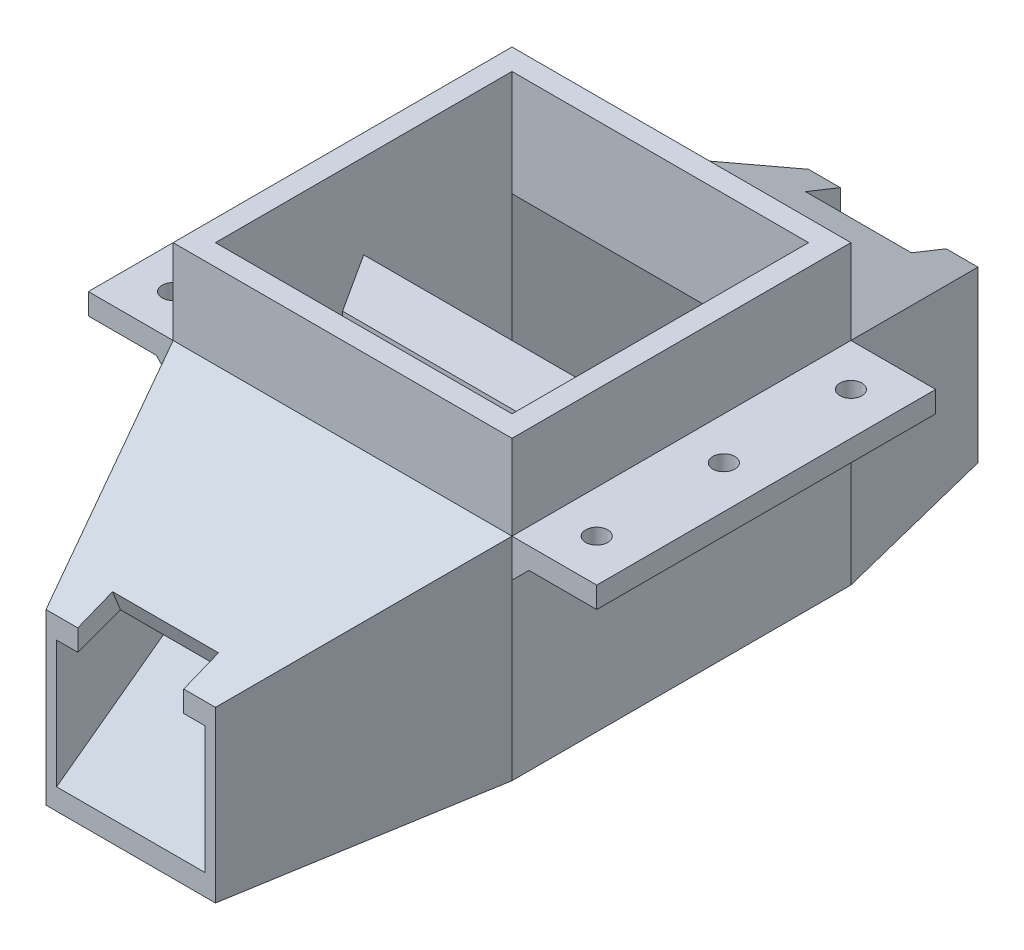
SolidWorks part; units mm, degrees
ref_plane "前视基准面" through (0, 0, 0) normal (0, 0, 1) x (1, 0, 0)
ref_plane "上视基准面" through (0, 0, 0) normal (0, 1, 0) x (1, 0, 0)
ref_plane "右视基准面" through (0, 0, 0) normal (1, 0, 0) x (0, 0, -1)
sketch "草图2" plane through (0, 0, 0) normal (0, 0, 1) x (1, 0, 0)
  line L0 (0, 0) -> (0, -45)
  line L1 (0, -45) -> (80, -45)
  line L2 (80, -45) -> (80, 0)
  line L3 (80, 0) -> (100, 0)
  line L4 (100, 0) -> (100, 5)
  line L5 (100, 5) -> (80, 5)
  line L6 (80, 5) -> (80, 25)
  line L7 (0, 25) -> (80, 25)
  line L13 (0, 25) -> (0, 5)
  line L14 (0, 5) -> (-20, 5)
  line L15 (-20, 5) -> (-20, 0)
  line L16 (-20, 0) -> (0, 0)
  dimension "D2" = 80
  dimension "D3" = 20
  dimension "D4" = 20
  dimension "D7" = 45
  dimension "D8" = 5
  dimension "D9" = 80
  dimension "D11" = 20
  dimension "D12" = 20
extrude "凸台-拉伸1" add sketch "草图2" along normal blind 80
sketch "草图4" plane through (0, 5, 0) normal (0, 1, 0) x (1, 0, 0)
  line L0 (0, 0) -> (-20, 0) construction
  line L3 (-20, -80) -> (-20, 0) construction
  circle A0 centre (-10, -40) radius 2.6
  circle A1 centre (-10, -70) radius 2.6
  circle A2 centre (-10, -10) radius 2.6
  circle A3 centre (90, -10) radius 2.6
  circle A4 centre (90, -40) radius 2.6
  circle A5 centre (90, -70) radius 2.6
  dimension "D1" = 5.2
  dimension "D2" = 5.2
  dimension "D5" = 5.2
  dimension "D3" = 40
  dimension "D4" = 30
  dimension "D6" = 10
  dimension "D7" = 10
  dimension "D8" = 10
  dimension "D9" = 2
extrude "切除-拉伸2" cut sketch "草图4" against normal blind 150
chamfer "倒角1" distance 4 angle 45 1 edges at (80, 0, 40)
chamfer "倒角2" distance 4 angle 45 1 edges at (0, 0, 40)
ref_plane "基准面1" through (0, 0, 40) normal (0, 0, 1) x (1, 0, 0)
sketch "草图8" plane through (0, 25, 0) normal (0, 1, 0) x (1, 0, 0)
  line L3 (80, -80) -> (0, -80) construction
  line L4 (5, -75) -> (75, -75)
  line L5 (5, -75) -> (5, -5)
  line L6 (5, -5) -> (75, -5)
  line L7 (75, -75) -> (75, -5)
  line L8 (0, -80) -> (0, 0) construction
  dimension "D1" = 5
  dimension "D3" = 70
  dimension "D2" = 5
  dimension "D4" = 70
extrude "切除-拉伸3" cut sketch "草图8" against normal blind 70
sketch "草图10" plane through (0, 0, 0) normal (0, 0, -1) x (-1, 0, 0)
ref_plane "基准面2" through (0, 0, -50) normal (0, 0, -1) x (-1, 0, 0)
sketch "草图17" plane through (0, 0, 0) normal (0, 0, -1) x (-1, 0, 0)
  line L1 (-80, 5) -> (0, 5)
  line L2 (-80, 5) -> (-80, -45)
  line L3 (-80, -45) -> (0, -45)
  line L4 (0, 5) -> (0, -45)
sketch "草图19" plane through (0, 0, -50) normal (0, 0, -1) x (-1, 0, 0)
  line L0 (-80, 5) -> (-80, -45) construction
  line L1 (-60, -15) -> (-20, -15)
  line L2 (-60, -15) -> (-60, -55)
  line L3 (-60, -55) -> (-20, -55)
  line L4 (-20, -15) -> (-20, -55)
  line L5 (-80, 5) -> (0, 5) construction
  dimension "D1" = 40
  dimension "D2" = 40
  dimension "D3" = 20
  dimension "D4" = 20
loft "放样3" add profiles "草图19", "草图17"
sketch "草图20" plane through (0, 0, 5) normal (0, 0, 1) x (1, 0, 0)
  line L0 (5, -45) -> (5, 25) construction
  line L1 (5, 0) -> (75, 0)
  line L2 (5, 0) -> (5, -40)
  line L3 (5, -40) -> (75, -40)
  line L4 (75, 0) -> (75, -40)
  line L5 (75, -45) -> (75, 25) construction
  line L6 (75, -45) -> (5, -45) construction
  dimension "D1" = 40
  dimension "D2" = 5
sketch "草图21" plane through (0, 0, -50) normal (0, 0, -1) x (-1, 0, 0)
  line L0 (-60, -55) -> (-20, -55) construction
  line L1 (-57.5, -20) -> (-22.5, -20)
  line L2 (-57.5, -20) -> (-57.5, -50)
  line L3 (-57.5, -50) -> (-22.5, -50)
  line L4 (-22.5, -20) -> (-22.5, -50)
  line L5 (-20, -15) -> (-60, -15) construction
  line L6 (-20, -55) -> (-20, -15) construction
  line L7 (-60, -15) -> (-60, -55) construction
  dimension "D1" = 5
  dimension "D2" = 5
  dimension "D3" = 2.5
  dimension "D4" = 2.5
sketch "草图22" plane through (80, 0, 0) normal (1, 0, 0) x (0, 0, -1)
  line L0 (-80, -45) -> (0, -45)
  line L1 (0, -45) -> (0, -40)
  line L2 (0, -45) -> (0, -4) construction
  line L3 (0, -40) -> (-40, -32)
  line L4 (-40, 55) -> (-40, -55) construction
  line L5 (-40, -32) -> (-80, -40)
  line L6 (-80, -45) -> (-80, -4) construction
  line L7 (-80, -40) -> (-80, -45)
  line L9 (50, -55) -> (0, -45) construction
  dimension "D1" = 5
  dimension "D2" = 5
  dimension "D3" = 40
extrude "凸台-拉伸3" add sketch "草图22" against normal blind 80
loft "切除-放样6" cut profiles "草图20", "草图21"
mirror "镜向1" about plane through (0, 0, 40) normal (0, 0, 1) of "切除-放样6", "放样3"
sketch "草图23" plane through (80, 0, 0) normal (1, 0, 0) x (0, 0, -1)
  line L0 (-45, -45) -> (-45, -4)
  line L1 (-80, -45) -> (0, -45) construction
  line L2 (0, -4) -> (-80, -4) construction
  line L3 (-45, -4) -> (-40, 5)
  line L4 (-80, 5) -> (0, 5) construction
  line L5 (-40, 5) -> (-35, -4)
  line L6 (-35, -4) -> (-35, -45)
  line L7 (-35, -45) -> (-45, -45)
  line L8 (-40, 55) -> (-40, -55) construction
  dimension "D1" = 10
  dimension "D2" = 5
  dimension "D3" = 29.055
  dimension "D4" = 29.055
  dimension "D5" = 29.055
extrude "凸台-拉伸4" add sketch "草图23" against normal blind 80
sketch "草图25" plane through (0, 31.8966, 12.7586) normal (0, 0.9285, 0.3714) x (1, 0, 0)
  line L0 (0, -72.4212) -> (80, -72.4212) construction
  line L1 (27.5, -142.5433) -> (52.5, -142.5433)
  line L2 (27.5, -142.5433) -> (27.5, -117.4212)
  line L3 (27.5, -117.4212) -> (52.5, -117.4212)
  line L4 (52.5, -142.5433) -> (52.5, -117.4212)
  line L5 (57.5, -128.1298) -> (57.5, -139.2715) construction
  line L6 (22.5, -139.2715) -> (22.5, -128.1298) construction
  dimension "D1" = 45
  dimension "D2" = 25
  dimension "D3" = 5
  dimension "D4" = 5
extrude "切除-拉伸8" cut sketch "草图25" against normal blind 20
mirror "镜向2" about plane through (0, 0, 40) normal (0, 0, 1) of "切除-拉伸8"
